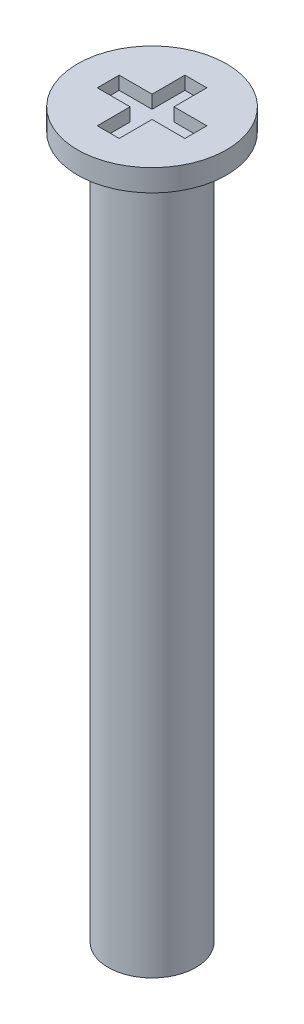
SolidWorks part; units mm, degrees
material "S45C"
ref_plane "正面" through (0, 0, 0) normal (0, 0, 1) x (1, 0, 0)
ref_plane "平面" through (0, 0, 0) normal (0, 1, 0) x (1, 0, 0)
ref_plane "右側面" through (0, 0, 0) normal (1, 0, 0) x (0, 0, -1)
sketch "ｽｹｯﾁ1" plane through (0, 0, 0) normal (0, 0, 1) x (1, 0, 0)
  line L0 (0, 0) -> (1.7, 0)
  line L1 (1.7, 0) -> (1.7, -0.5)
  line L2 (1.7, -0.5) -> (1, -0.5)
  line L3 (1, -0.5) -> (1, -16.5)
  line L4 (1, -16.5) -> (0, -16.5)
  line L5 (0, -16.5) -> (0, 0)
  dimension "D1" = 1.7
  dimension "D2" = 0.5
  dimension "D3" = 1
  dimension "D4" = 16
revolve "回転1" add sketch "ｽｹｯﾁ1" angle 360 about L5
sketch "ｽｹｯﾁ2" plane through (0, 0, 0) normal (0, 1, 0) x (1, 0, 0)
  line L1 (-0.25, 0) -> (0.25, 0)
  line L2 (-0.25, 0) -> (-0.25, 1)
  line L3 (-0.25, 1) -> (0.25, 1)
  line L4 (0.25, 0) -> (0.25, 1)
  line L5 (-0.25, 0) -> (0.25, 1) construction
  line L6 (-0.25, 1) -> (0.25, 0) construction
  point P4 (0, 0.5)
  dimension "D1" = 0
  dimension "D2" = 0.5
  dimension "D3" = 1
  dimension "D4" = 0
extrude "ｶｯﾄ - 押し出し1" cut sketch "ｽｹｯﾁ2" against normal blind 0.3
pattern_circular "円形ﾊﾟﾀｰﾝ1" count 4 over 360 about axis through (0, 0, 0) along (0, 1, 0) of "ｶｯﾄ - 押し出し1"
